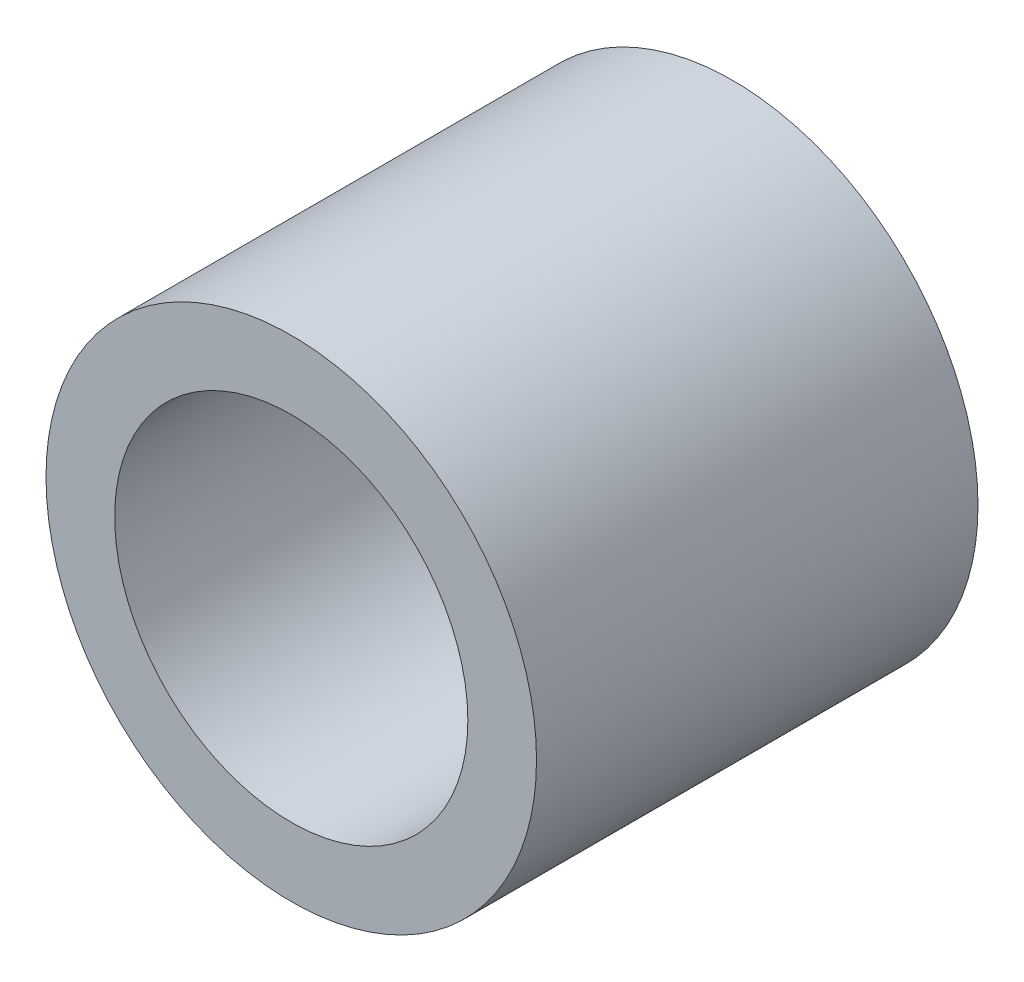
SolidWorks part; units mm, degrees
ref_plane "Front Plane" through (0, 0, 0) normal (0, 0, 1) x (1, 0, 0)
ref_plane "Top Plane" through (0, 0, 0) normal (0, 1, 0) x (1, 0, 0)
ref_plane "Right Plane" through (0, 0, 0) normal (1, 0, 0) x (0, 0, -1)
sketch "Sketch1" plane through (0, 0, 0) normal (0, 0, 1) x (1, 0, 0)
  circle A0 centre (0, 0) radius 6.35
  dimension "D1" = 12.7
extrude "Boss-Extrude1" add sketch "Sketch1" along normal blind 11.43
sketch "Sketch2" plane through (0, 0, 11.43) normal (0, 0, 1) x (1, 0, 0)
  circle A0 centre (0, 0) radius 4.572
  circle A1 centre (0, 0) radius 6.35 construction
  dimension "D1" = 1.778
extrude "Cut-Extrude1" cut sketch "Sketch2" against normal through all
